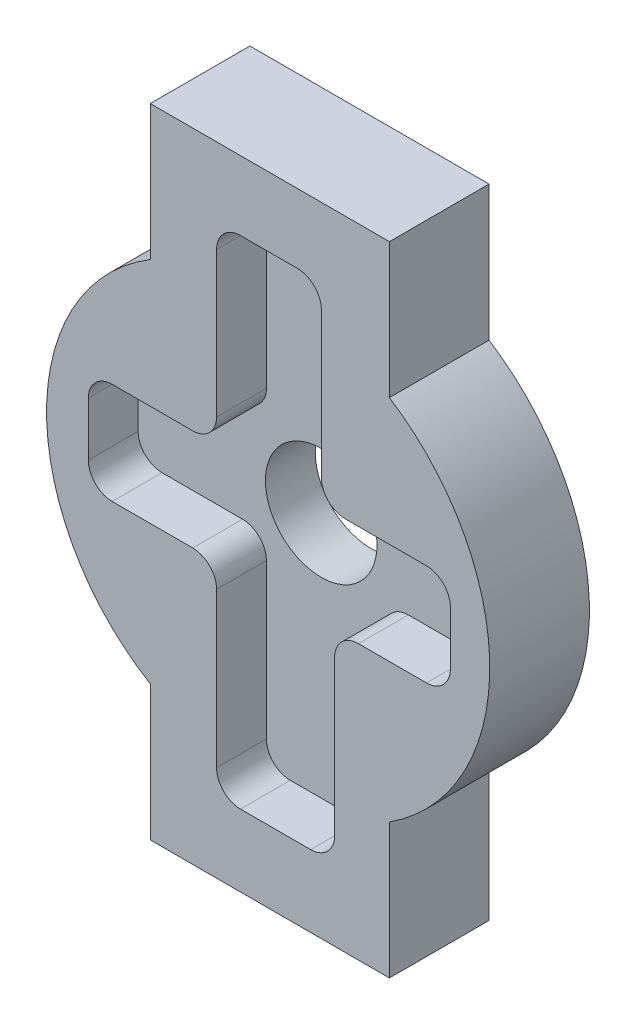
SolidWorks part; units mm, degrees
ref_plane "Front Plane" through (0, 0, 0) normal (0, 0, 1) x (1, 0, 0)
ref_plane "Top Plane" through (0, 0, 0) normal (0, 1, 0) x (1, 0, 0)
ref_plane "Right Plane" through (0, 0, 0) normal (1, 0, 0) x (0, 0, -1)
other "Graphic1"
other "object_1 (Open) -1"
ref_plane "Plane1" through (0, 0, 10) normal (0, 0, 1) x (1, 0, 0)
sketch "Sketch1" plane through (0, 0, 10) normal (0, 0, 1) x (1, 0, 0)
  line L0 (-246.9356, 240) -> (-246.9356, 200) construction
  line L1 (-257.9579, 223.6814) -> (-221.137, 223.6814) construction
  line L2 (-253, 240) -> (-241, 240)
  line L3 (-241, 240) -> (-241, 233.2195)
  line L4 (-241, 214.7805) -> (-241, 208)
  line L5 (-241, 208) -> (-253, 208)
  line L6 (-253, 208) -> (-253, 214.7805)
  line L7 (-253, 240) -> (-253, 233.2195)
  arc A0 (-241, 233.2195) -> (-241, 214.7805) centre (-246.9226, 224) cw
  arc A1 (-253, 233.2195) -> (-253, 214.7805) centre (-247.4317, 224) ccw
  circle A2 centre (-246.9226, 224) radius 2.8
  dimension "D1" = 12
extrude "Boss-Extrude1" add sketch "Sketch1" along normal blind 5
sketch "Sketch2" plane through (0, 0, 15) normal (0, 0, 1) x (1, 0, 0)
  line L0 (-249.6717, 236.5268) -> (-244.415, 236.5268)
  line L1 (-244.415, 236.5268) -> (-244.415, 226.8433)
  line L2 (-244.415, 226.8433) -> (-237.9409, 226.8433)
  line L3 (-237.9409, 226.8433) -> (-237.9409, 221.7526)
  line L4 (-237.9409, 221.7526) -> (-243.751, 221.7526)
  line L5 (-243.751, 221.7526) -> (-243.751, 211.6041)
  line L6 (-243.751, 211.6041) -> (-249.6717, 211.6041)
  line L7 (-249.6717, 211.6041) -> (-249.6717, 221.7526)
  line L8 (-249.6717, 221.7526) -> (-256.1089, 221.7526)
  line L9 (-256.1089, 221.7526) -> (-256.1089, 226.8433)
  line L10 (-256.1089, 226.8433) -> (-249.6717, 226.8433)
  line L11 (-249.6717, 226.8433) -> (-249.6717, 236.5268)
extrude "Cut-Extrude1" cut sketch "Sketch2" against normal blind 2.5
fillet "Fillet1" radius 1.2 12 edges at (-256.1089, 226.8433, 13.75) (-256.1089, 221.7526, 13.75) (-249.6717, 221.7526, 13.75) (-249.6717, 211.6041, 13.75) (-243.751, 211.6041, 13.75) (-243.751, 221.7526, 13.75) (-237.9409, 221.7526, 13.75) (-237.9409, 226.8433, 13.75) (-244.415, 226.8433, 13.75) (-249.6717, 226.8433, 13.75) (-249.6717, 236.5268, 13.75) (-244.415, 236.5268, 13.75)
